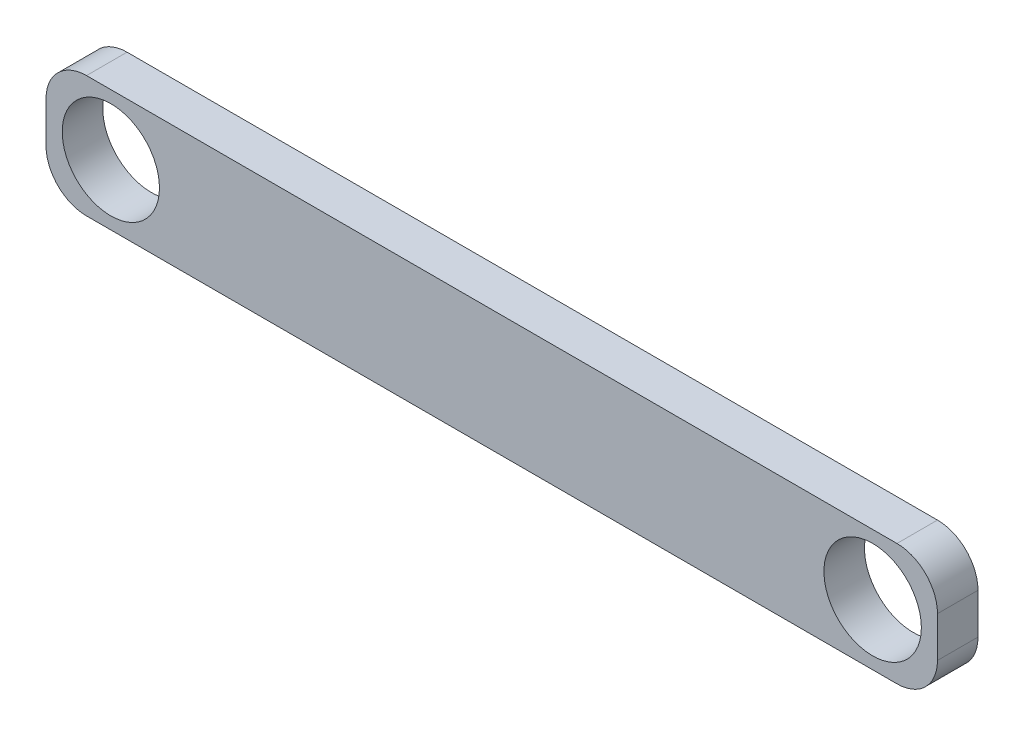
SolidWorks part; units mm, degrees
ref_plane "前视基准面" through (0, 0, 0) normal (0, 0, 1) x (1, 0, 0)
ref_plane "上视基准面" through (0, 0, 0) normal (0, 1, 0) x (1, 0, 0)
ref_plane "右视基准面" through (0, 0, 0) normal (1, 0, 0) x (0, 0, -1)
sketch "草图1" plane through (0, 0, 0) normal (0, 0, 1) x (1, 0, 0)
  line L0 (5, 15) -> (5, 0)
  line L1 (5, 0) -> (105, 0)
  line L2 (0, 5) -> (0, 10)
  line L3 (5, 15) -> (105, 15)
  line L4 (110, 5) -> (110, 10)
  line L5 (0, 7.5) -> (5, 7.5)
  line L6 (5, 7.5) -> (110, 7.5)
  line L7 (105, 15) -> (105, 7.5)
  line L8 (105, 7.5) -> (105, 0)
  line L9 (5, 7.5) -> (8, 7.5)
  line L10 (105, 7.5) -> (102, 7.5)
  arc A0 (105, 0) -> (110, 5) centre (105, 5) ccw
  arc A1 (105, 15) -> (110, 10) centre (105, 10) cw
  arc A2 (5, 0) -> (0, 5) centre (5, 5) cw
  arc A3 (0, 10) -> (5, 15) centre (5, 10) cw
  circle A4 centre (8, 7.5) radius 6
  circle A5 centre (8, 7.5) radius 6
  circle A6 centre (102, 7.5) radius 6.0107
  point P11 (0, 0)
  dimension "D1" = 5
  dimension "D5" = 3
  dimension "D2" = 100
  dimension "D3" = 15
  dimension "D4" = 3
extrude "凸台-拉伸1" add sketch "草图1" along normal blind 5 contours A6 L6 A4 L0 L1 L8 | A4 L5 L2 A2 L0 | A4 L0 A3 L2 L5 | A6 L7 L3 L0 A4 L6 | A6 L6 L4 A1 L7 | A6 L8 A0 L4 L6
sketch "草图2" plane through (0, 0, 0) normal (0, 0, 1) x (1, 0, 0)
